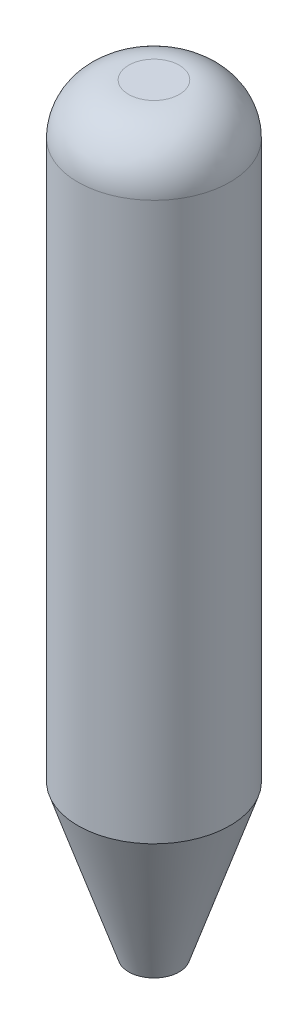
SolidWorks part; units mm, degrees
ref_plane "Alzado" through (0, 0, 0) normal (0, 0, 1) x (1, 0, 0)
ref_plane "Planta" through (0, 0, 0) normal (0, 1, 0) x (1, 0, 0)
ref_plane "Vista lateral" through (0, 0, 0) normal (1, 0, 0) x (0, 0, -1)
sketch "Croquis1" plane through (0, 0, 0) normal (0, 1, 0) x (1, 0, 0)
  circle A0 centre (0, 0) radius 15
  dimension "D1" = 30
extrude "Saliente-Extruir1" add sketch "Croquis1" along normal blind 150
fillet "Redondeo5" radius 10 1 edges at (0, 150, 15)
chamfer "Chaflán2" distance 10 distance2 30 1 edges at (0, 0, 15)
